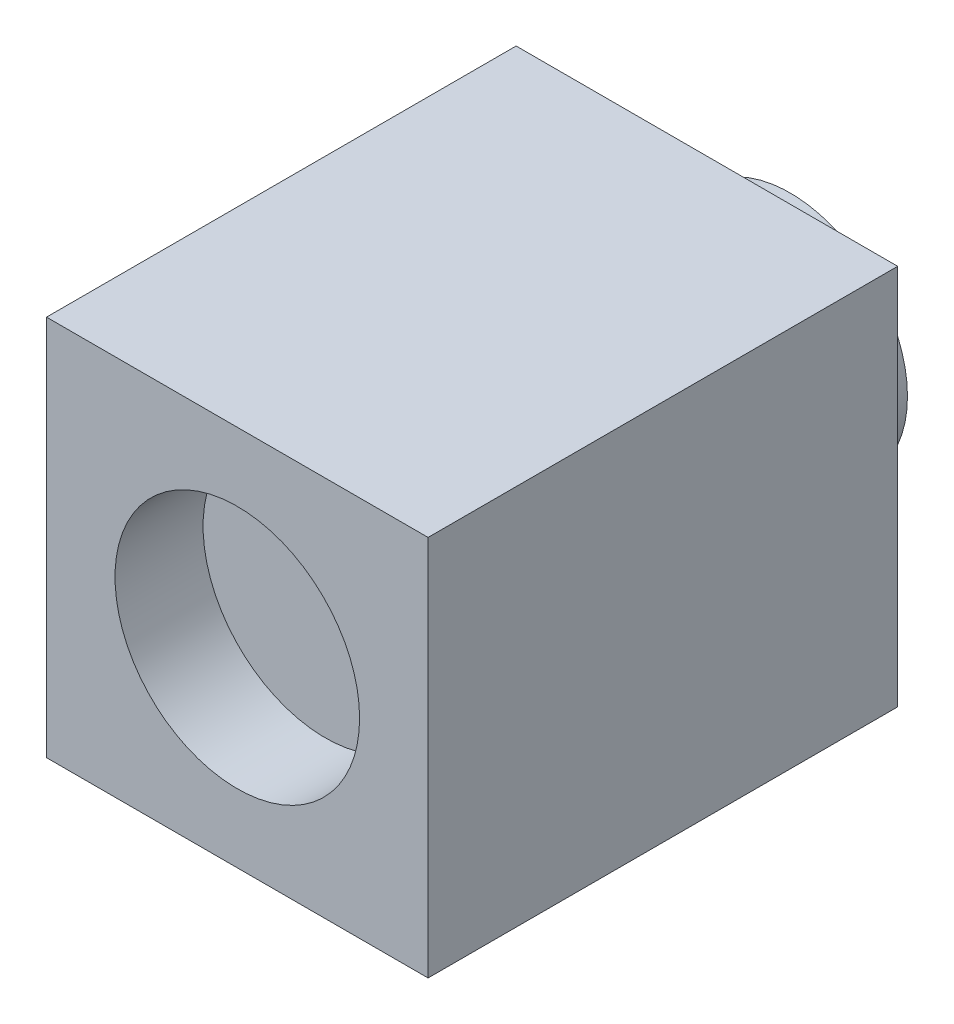
SolidWorks part; units mm, degrees
ref_plane "Спереди" through (0, 0, 0) normal (0, 0, 1) x (1, 0, 0)
ref_plane "Сверху" through (0, 0, 0) normal (0, 1, 0) x (1, 0, 0)
ref_plane "Справа" through (0, 0, 0) normal (1, 0, 0) x (0, 0, -1)
sketch "Эскиз1" plane through (0, 0, 0) normal (0, 0, 1) x (1, 0, 0)
  line L1 (-3.9, -3.9) -> (3.9, -3.9)
  line L2 (-3.9, -3.9) -> (-3.9, 3.9)
  line L3 (-3.9, 3.9) -> (3.9, 3.9)
  line L4 (3.9, -3.9) -> (3.9, 3.9)
  line L5 (-3.9, -3.9) -> (3.9, 3.9) construction
  line L6 (-3.9, 3.9) -> (3.9, -3.9) construction
  point P0 (0, 0)
  dimension "D1" = 7.8
  dimension "D2" = 7.8
extrude "Бобышка-Вытянуть1" add sketch "Эскиз1" along normal blind 9.6
sketch "Эскиз2" plane through (0, 0, 0) normal (0, 0, -1) x (-1, 0, 0)
  circle A0 centre (0, 0) radius 2.4
extrude "Бобышка-Вытянуть2" add sketch "Эскиз2" along normal blind 1.7
sketch "Эскиз3" plane through (0, 0, 9.6) normal (0, 0, 1) x (1, 0, 0)
  circle A0 centre (0, 0) radius 2.5
extrude "Вырез-Вытянуть1" cut sketch "Эскиз3" against normal blind 1.8
